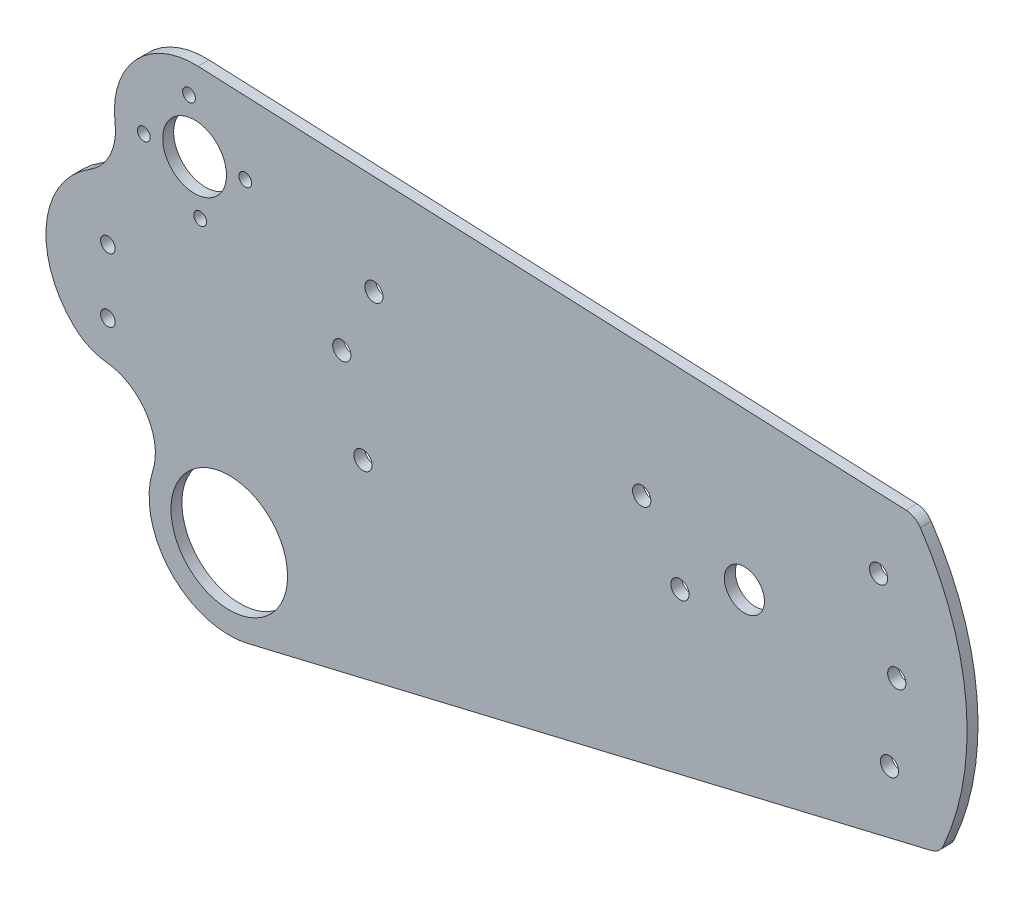
SolidWorks part; units mm, degrees
ref_plane "Front Plane" through (0, 0, 0) normal (0, 0, 1) x (1, 0, 0)
ref_plane "Top Plane" through (0, 0, 0) normal (0, 1, 0) x (1, 0, 0)
ref_plane "Right Plane" through (0, 0, 0) normal (1, 0, 0) x (0, 0, -1)
sketch "Sketch1" plane through (0, 0, 0) normal (0, 0, 1) x (1, 0, 0)
  line L0 (83.305, -33.5) -> (-137.2004, -33.5) construction
  line L1 (-113.5603, 49.4797) -> (80.7216, 41.1353)
  line L2 (-116.9253, 49.6243) -> (-102.5652, -81.605) construction
  line L3 (-99.3111, -80.7362) -> (92.6556, -29.4815) construction
  line L4 (75.1114, 41.3762) -> (83.1431, -32.0213) construction
  line L5 (-109.7453, -15.9904) -> (79.1273, 4.6775) construction
  line L6 (91, -33.5) -> (-88.5, -33.5) construction
  line L7 (-97.4673, 5.5) -> (-155.3054, 5.5) construction
  line L8 (-138.3, -14) -> (-155.3054, -14) construction
  line L9 (-138.3, 5.5) -> (-138.3, -33.5) construction
  line L10 (-155.3054, 5.5) -> (-155.3054, -33.5) construction
  line L11 (36.3824, 33.5) -> (36.3824, -33.5) construction
  line L12 (-111.8477, -83.7242) -> (87.5903, -36.3264)
  line L13 (-91.5, 33.5) -> (88, 33.5) construction
  line L14 (-68.3, -21.5) -> (-108.6591, -25.9164) construction
  circle A0 centre (36.3824, 0) radius 5.5
  circle A1 centre (-114.5043, 27.5) radius 14 construction
  circle A2 centre (-104.9862, -59.4808) radius 14 construction
  arc A3 (-91.5, 33.5) -> (-88.5, -33.5) centre (-18.0922, 3.2198) ccw construction
  circle A4 centre (-68.3, -21.5) radius 2.5
  circle A5 centre (-68.3, -21.5) radius 2.5 construction
  circle A6 centre (-138.3, -5.25) radius 2
  circle A7 centre (-138.3, -22.75) radius 2
  arc A8 (-143.371, 10.0569) -> (-147.5429, -29.3643) centre (-130.3054, -11.2571) ccw
  arc A9 (-147.5429, -29.3643) -> (-137.2004, -33.5) centre (-137.2004, -18.5) ccw
  circle A10 centre (-114.5043, 27.5) radius 22
  arc A11 (87.5903, -36.3264) -> (91, -33.5) centre (86.4343, -31.4619) ccw
  circle A12 centre (-104.9862, -59.4808) radius 22
  arc A13 (91, -33.5) -> (84.6484, 38.9414) centre (22.6589, -2.9929) ccw
  arc A14 (91, -33.5) -> (88, 33.5) centre (22.6589, -2.9929) ccw construction
  arc A15 (84.6484, 38.9414) -> (80.7216, 41.1353) centre (80.507, 36.1399) ccw
  arc A17 (-125.9657, -52.858) -> (-138.7351, -33.4213) centre (-140.2699, -48.3426) ccw
  arc A18 (-143.371, 10.0569) -> (-136.3295, 24.7324) centre (-151.2104, 22.8454) ccw
  circle A19 centre (-74.1, 1.7) radius 2.5
  circle A20 centre (-65.3, 20) radius 2.5
  circle A21 centre (8.2, 8.3) radius 2.5
  circle A23 centre (18.7, -8.7) radius 2.5
  circle A25 centre (78.2, -0.1) radius 2.5
  circle A26 centre (76.2, -22) radius 2.5
  circle A27 centre (73.2, 22.3) radius 2.5
  circle A28 centre (73.2, 22.3) radius 2.5 construction
  circle A29 centre (78.2, -0.1) radius 2.5 construction
  circle A31 centre (8.2, 8.3) radius 2.5 construction
  circle A32 centre (18.7, -8.7) radius 2.5 construction
  circle A33 centre (76.2, -22) radius 2.5 construction
  circle A34 centre (-74.1, 1.7) radius 2.5 construction
  circle A35 centre (-65.3, 20) radius 2.5 construction
  circle A36 centre (-116.0272, 41.4169) radius 1.75
  circle A37 centre (-100.5874, 29.0229) radius 1.75
  circle A38 centre (-112.9814, 13.5831) radius 1.75
  circle A39 centre (-128.4212, 25.9771) radius 1.75
  circle A40 centre (-106.5091, -45.5639) radius 1.75
  circle A41 centre (-91.0693, -57.9579) radius 1.75
  circle A42 centre (-103.4633, -73.3977) radius 1.75
  circle A43 centre (-118.9031, -61.0037) radius 1.75
  circle A44 centre (36.3824, 0) radius 35 construction
  circle A45 centre (36.3824, 0) radius 43
  circle A49 centre (-104.9862, -59.4808) radius 16
  circle A50 centre (-114.5043, 27.5) radius 16 construction
  circle A51 centre (-114.5043, 27.5) radius 8.75
  circle A52 centre (-104.9862, -59.4808) radius 8.75
  arc A53 (91, -33.5) -> (88, 33.5) centre (22.6589, -2.9929) ccw construction
  point P52 (79.1273, 4.6775)
  point P109 (-114.5043, 27.5)
  point P118 (-104.9862, -59.4808)
  dimension "D5" = 4
  dimension "D6" = 25
  dimension "D9" = 15
  dimension "D13" = 10
  dimension "D14" = 28
  dimension "D11" = 44
  dimension "D15" = 3.5
  dimension "D12" = 70
  dimension "D19" = 11
  dimension "D20" = 17.5
  dimension "D22" = 32
  dimension "D2" = 39
  dimension "D3" = 70
  dimension "D4" = 17.5
  dimension "D7" = 14
  dimension "D8" = 10
  dimension "D10" = 87.5
  dimension "D21" = 190
  dimension "D23" = 40.6
  dimension "D18" = 8
  dimension "D16" = 4
  dimension "D17" = 4
extrude "Boss-Extrude1" add sketch "Sketch1" along normal blind 3
